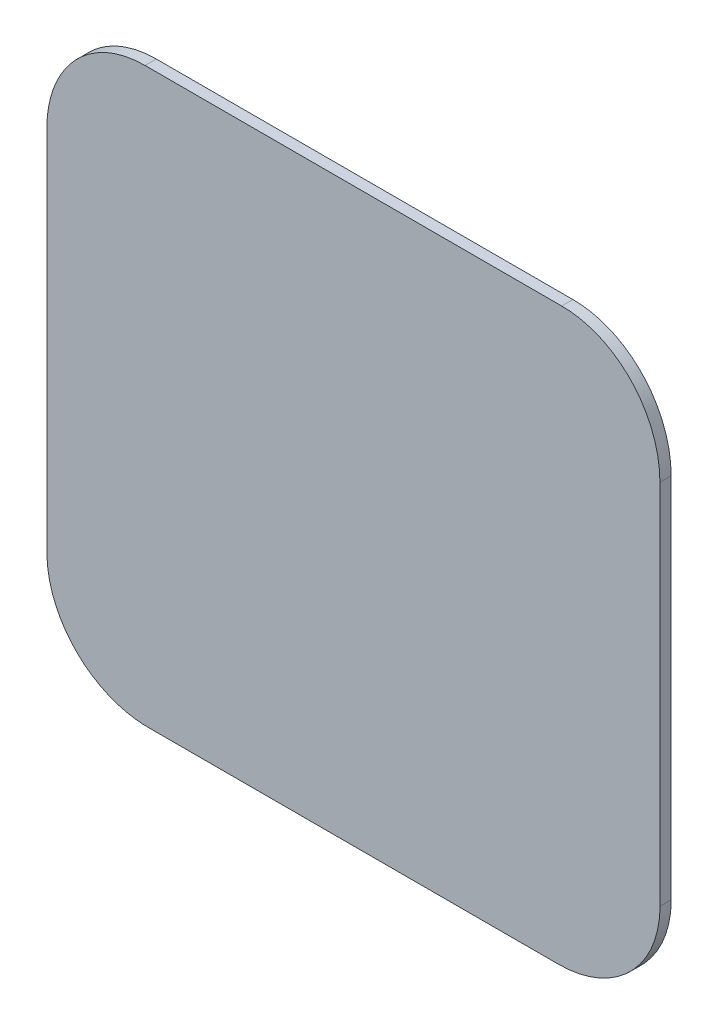
SolidWorks part; units mm, degrees
material "Beech"
ref_plane "Front Plane" through (0, 0, 0) normal (0, 0, 1) x (1, 0, 0)
ref_plane "Top Plane" through (0, 0, 0) normal (0, 1, 0) x (1, 0, 0)
ref_plane "Right Plane" through (0, 0, 0) normal (1, 0, 0) x (0, 0, -1)
sketch "Sketch1" plane through (0, 0, 0) normal (0, 0, 1) x (1, 0, 0)
  line L0 (-105.3184, 124.9067) -> (-105.3184, -72.5)
  line L1 (-105.3184, -72.5) -> (103.4563, -72.5)
  line L2 (103.4563, -72.5) -> (103.4563, 124.9067)
  line L3 (103.4563, 124.9067) -> (-105.3184, 124.9067)
  line L4 (-80, 72.5) -> (-80, -72.5)
  line L5 (-80, -72.5) -> (80, -72.5)
  line L6 (80, -72.5) -> (80, 72.5)
  line L7 (80, 72.5) -> (-80, 72.5)
  line L8 (-80, 72.5) -> (-80, -72.5) construction
  line L9 (-80, -72.5) -> (80, -72.5) construction
  line L10 (80, -72.5) -> (80, 72.5) construction
  point P6 (103.4563, -72.5)
  point P11 (-105.3184, -72.5)
  point P12 (-26.5962, 65.6232)
  point P25 (-25, 60.7089)
  dimension "D1" = 0
extrude "Boss-Extrude1" add sketch "Sketch1" along normal blind 3
sketch3d "3DSketch1"
  line L0 (-81.9859, -42.5, 3) -> (-81.9859, 55.6964, 3)
  line L1 (-81.9859, -42.5, 3) -> (-81.9859, 55.6964, 3)
  line L2 (55.7121, 83.4001, 3) -> (-55.7121, 83.4001, 3)
  line L3 (55.7121, 83.4001, 3) -> (-55.7121, 83.4001, 3)
  line L4 (81.9859, 55.6964, 3) -> (81.9859, -42.5, 3)
  line L5 (81.9859, 55.6964, 3) -> (81.9859, -42.5, 3)
  line L7 (-57.3103, -69.3887, 3) -> (54.8518, -69.5, 2.9231)
  spline S0 degree 3 poles (1820.8216, -546.1374, 3) (335.0368, -201.7655, 3) (-98.3461, -32.8647, 3) (-81.3627, 61.8369, 3) (-81.1687, 62.6966, 3) (-80.8177, 63.9762, 3) (-80.6907, 64.401, 3) (-80.4161, 65.2473, 3) (-80.2683, 65.6692, 3) (-79.4853, 67.7479, 3) (-78.7138, 69.3299, 3) (-77.3377, 71.581, 3) (-76.8423, 72.3109, 3) (-75.7748, 73.7279, 3) (-75.2005, 74.4167, 3) (-73.3997, 76.3696, 3) (-72.0849, 77.5372, 3) (-69.9389, 79.0843, 3) (-69.1937, 79.5661, 3) (-67.6448, 80.4559, 3) (-66.8542, 80.8565, 3) (-64.4352, 81.9294, 3) (-62.7601, 82.474, 3) (-60.5861, 82.9359, 3) (-60.1462, 83.0173, 3) (-59.265, 83.1566, 3) (-58.8233, 83.2146, 3) (40.0623, 93.5712, 3) (189.0947, -468.1443, 3) (411.2832, -1857.0498, 3) knots -6.645974 -6.645974 -6.645974 -6.645974 0.125 0.125 0.1875 0.1875 0.21875 0.21875 0.25 0.25 0.375 0.375 0.4375 0.4375 0.5 0.5 0.625 0.625 0.6875 0.6875 0.75 0.75 0.875 0.875 0.90625 0.90625 0.9375 0.9375 7.886578 7.886578 7.886578 7.886578 only from (-81.9859, 55.6964, 3) to (-55.7121, 83.4001, 3)
  spline S1 degree 3 poles (-81.9859, 55.6964, 3) (-81.9859, 57.4805, 3) (-81.8287, 59.2384, 3) (-81.3627, 61.8369, 3) (-81.1687, 62.6966, 3) (-80.8177, 63.9762, 3) (-80.6907, 64.401, 3) (-80.4161, 65.2473, 3) (-80.2683, 65.6692, 3) (-79.4853, 67.7479, 3) (-78.7138, 69.3299, 3) (-77.3377, 71.581, 3) (-76.8423, 72.3109, 3) (-75.7748, 73.7279, 3) (-75.2005, 74.4167, 3) (-73.3997, 76.3696, 3) (-72.0849, 77.5372, 3) (-69.9389, 79.0843, 3) (-69.1937, 79.5661, 3) (-67.6448, 80.4559, 3) (-66.8542, 80.8565, 3) (-64.4352, 81.9294, 3) (-62.7601, 82.474, 3) (-60.5861, 82.9359, 3) (-60.1462, 83.0173, 3) (-59.265, 83.1566, 3) (-58.8233, 83.2146, 3) (-57.4952, 83.3537, 3) (-56.6057, 83.4001, 3) (-55.7121, 83.4001, 3) knots 0 0 0 0 0.125 0.125 0.1875 0.1875 0.21875 0.21875 0.25 0.25 0.375 0.375 0.4375 0.4375 0.5 0.5 0.625 0.625 0.6875 0.6875 0.75 0.75 0.875 0.875 0.90625 0.90625 0.9375 0.9375 1 1 1 1
  spline S2 degree 3 poles (-528.9221, -1825.3944, 3) (-184.3393, -319.6628, 3) (-24.3861, 100.8215, 3) (61.8362, 82.6719, 3) (62.6902, 82.4455, 3) (63.9595, 82.0364, 3) (64.3815, 81.8881, 3) (65.2121, 81.5713, 3) (65.6217, 81.4027, 3) (67.6418, 80.509, 3) (69.1693, 79.6343, 3) (71.3289, 78.0845, 3) (72.0292, 77.5252, 3) (73.3559, 76.3503, 3) (74.6158, 75.1151, 3) (75.7463, 73.7631, 3) (76.5459, 72.7055, 3) (76.8044, 72.3457, 3) (77.3052, 71.6114, 3) (77.5479, 71.2361, 3) (78.709, 69.3415, 3) (79.4804, 67.7568, 3) (80.415, 65.282, 3) (80.6891, 64.4407, 3) (81.1619, 62.725, 3) (81.3588, 61.8562, 3) (101.0439, -47.6059, 3) (-486.6496, -233.904, 3) (-1829.4053, -516.8289, 3) knots -6.06625 -6.06625 -6.06625 -6.06625 0.125 0.125 0.1875 0.1875 0.21875 0.21875 0.25 0.25 0.375 0.375 0.4375 0.4375 0.5 0.5625 0.5625 0.59375 0.59375 0.625 0.625 0.75 0.75 0.8125 0.8125 0.875 0.875 8.663755 8.663755 8.663755 8.663755 only from (55.7121, 83.4001, 3) to (81.9859, 55.6964, 3)
  spline S3 degree 3 poles (55.7121, 83.4001, 3) (57.4972, 83.4001, 3) (59.2511, 83.2161, 3) (61.8362, 82.6719, 3) (62.6902, 82.4455, 3) (63.9595, 82.0364, 3) (64.3815, 81.8881, 3) (65.2121, 81.5713, 3) (65.6217, 81.4027, 3) (67.6418, 80.509, 3) (69.1693, 79.6343, 3) (71.3289, 78.0845, 3) (72.0292, 77.5252, 3) (73.3559, 76.3503, 3) (74.6158, 75.1151, 3) (75.7463, 73.7631, 3) (76.5459, 72.7055, 3) (76.8044, 72.3457, 3) (77.3052, 71.6114, 3) (77.5479, 71.2361, 3) (78.709, 69.3415, 3) (79.4804, 67.7568, 3) (80.415, 65.282, 3) (80.6891, 64.4407, 3) (81.1619, 62.725, 3) (81.3588, 61.8562, 3) (81.8289, 59.242, 3) (81.9859, 57.4793, 3) (81.9859, 55.6964, 3) knots 0 0 0 0 0.125 0.125 0.1875 0.1875 0.21875 0.21875 0.25 0.25 0.375 0.375 0.4375 0.4375 0.5 0.5625 0.5625 0.59375 0.59375 0.625 0.625 0.75 0.75 0.8125 0.8125 0.875 0.875 1 1 1 1
  spline S4 degree 3 poles (-1829.33, 534.0708, 0.1379) (-272.689, 183.4966, 2.5914) (97.9924, 34.891, 3.1086) (81.2915, -48.6371, 2.9924) (81.0761, -49.494, 2.9912) (80.558, -51.193, 2.9885) (80.2541, -52.037, 2.9871) (79.2303, -54.4912, 2.9827) (78.3951, -56.0428, 2.9796) (77.1621, -57.8776, 2.9754) (76.906, -58.2393, 2.9746) (76.3743, -58.9519, 2.9729) (76.098, -59.3038, 2.9721) (75.2465, -60.3345, 2.9695) (74.6493, -60.9884, 2.9677) (72.7714, -62.8535, 2.9624) (71.4054, -63.9693, 2.9588) (69.5521, -65.2005, 2.9542) (69.1732, -65.439, 2.9532) (68.4083, -65.8945, 2.9514) (68.0217, -66.112, 2.9504) (66.8492, -66.7346, 2.9477) (65.2528, -67.4846, 2.944) (63.591, -68.0769, 2.9404) (62.3198, -68.4612, 2.9377) (61.8919, -68.5793, 2.9368) (61.0277, -68.7951, 2.935) (60.591, -68.8928, 2.9341) (-41.1771, -89.06, 2.7294) (-208.0924, 470.357, 3.0035) (-468.5475, 1856.2863, 3.9593) knots -5.853401 -5.853401 -5.853401 -5.853401 0.125 0.125 0.1875 0.1875 0.25 0.25 0.375 0.375 0.40625 0.40625 0.4375 0.4375 0.5 0.5 0.625 0.625 0.65625 0.65625 0.6875 0.6875 0.75 0.8125 0.8125 0.84375 0.84375 0.875 0.875 8.12185 8.12185 8.12185 8.12185 only from (81.9859, -42.5, 3) to (54.8518, -69.5, 2.9231)
  spline S5 degree 3 poles (81.9859, -42.5, 3) (81.9862, -44.2873, 2.9982) (81.8099, -46.0445, 2.996) (81.2915, -48.6371, 2.9924) (81.0761, -49.494, 2.9912) (80.558, -51.193, 2.9885) (80.2541, -52.037, 2.9871) (79.2303, -54.4912, 2.9827) (78.3951, -56.0428, 2.9796) (77.1621, -57.8776, 2.9754) (76.906, -58.2393, 2.9746) (76.3743, -58.9519, 2.9729) (76.098, -59.3038, 2.9721) (75.2465, -60.3345, 2.9695) (74.6493, -60.9884, 2.9677) (72.7714, -62.8535, 2.9624) (71.4054, -63.9693, 2.9588) (69.5521, -65.2005, 2.9542) (69.1732, -65.439, 2.9532) (68.4083, -65.8945, 2.9514) (68.0217, -66.112, 2.9504) (66.8492, -66.7346, 2.9477) (65.2528, -67.4846, 2.944) (63.591, -68.0769, 2.9404) (62.3198, -68.4612, 2.9377) (61.8919, -68.5793, 2.9368) (61.0277, -68.7951, 2.935) (60.591, -68.8928, 2.9341) (58.4062, -69.3258, 2.9298) (56.6388, -69.4997, 2.9264) (54.8518, -69.5, 2.9231) knots 0 0 0 0 0.125 0.125 0.1875 0.1875 0.25 0.25 0.375 0.375 0.40625 0.40625 0.4375 0.4375 0.5 0.5 0.625 0.625 0.65625 0.65625 0.6875 0.6875 0.75 0.8125 0.8125 0.84375 0.84375 0.875 0.875 1 1 1 1
  spline S6 degree 3 poles (1829.2313, 534.3813, 3) (272.6605, 183.5658, 3) (-98.0057, 34.895, 3) (-81.2905, -48.6379, 3) (-81.0749, -49.4949, 3) (-80.5565, -51.1941, 3) (-80.2523, -52.0382, 3) (-79.228, -54.4927, 3) (-78.3924, -56.0444, 3) (-77.159, -57.8793, 3) (-76.9028, -58.2409, 3) (-76.3709, -58.9536, 3) (-76.0945, -59.3055, 3) (-75.2428, -60.3362, 3) (-74.6453, -60.9901, 3) (-72.7668, -62.8553, 3) (-71.4005, -63.9709, 3) (-69.5467, -65.2021, 3) (-69.1677, -65.4405, 3) (-68.4027, -65.896, 3) (-68.0159, -66.1135, 3) (-66.8432, -66.736, 3) (-65.2464, -67.4858, 3) (-63.5842, -68.078, 3) (-62.3128, -68.4622, 3) (-61.8848, -68.5802, 3) (-61.0204, -68.7959, 3) (-60.5836, -68.8936, 3) (41.1964, -89.047, 3) (208.0355, 470.4038, 3) (468.2869, 1856.3789, 3) knots -5.853011 -5.853011 -5.853011 -5.853011 0.125 0.125 0.1875 0.1875 0.25 0.25 0.375 0.375 0.40625 0.40625 0.4375 0.4375 0.5 0.5 0.625 0.625 0.65625 0.65625 0.6875 0.6875 0.75 0.8125 0.8125 0.84375 0.84375 0.875 0.875 8.121359 8.121359 8.121359 8.121359 only from (-81.9859, -42.5, 3) to (-54.8435, -69.5, 3)
  spline S7 degree 3 poles (-81.9859, -42.5, 3) (-81.9859, -44.2876, 3) (-81.8093, -46.045, 3) (-81.2905, -48.6379, 3) (-81.0749, -49.4949, 3) (-80.5565, -51.1941, 3) (-80.2523, -52.0382, 3) (-79.228, -54.4927, 3) (-78.3924, -56.0444, 3) (-77.159, -57.8793, 3) (-76.9028, -58.2409, 3) (-76.3709, -58.9536, 3) (-76.0945, -59.3055, 3) (-75.2428, -60.3362, 3) (-74.6453, -60.9901, 3) (-72.7668, -62.8553, 3) (-71.4005, -63.9709, 3) (-69.5467, -65.2021, 3) (-69.1677, -65.4405, 3) (-68.4027, -65.896, 3) (-68.0159, -66.1135, 3) (-66.8432, -66.736, 3) (-65.2464, -67.4858, 3) (-63.5842, -68.078, 3) (-62.3128, -68.4622, 3) (-61.8848, -68.5802, 3) (-61.0204, -68.7959, 3) (-60.5836, -68.8936, 3) (-59.2068, -69.1662, 3) (-58.2613, -69.3025, 3) (-57.3103, -69.3887, 3) knots 0 0 0 0 0.125 0.125 0.1875 0.1875 0.25 0.25 0.375 0.375 0.40625 0.40625 0.4375 0.4375 0.5 0.5 0.625 0.625 0.65625 0.65625 0.6875 0.6875 0.75 0.8125 0.8125 0.84375 0.84375 0.875 0.875 0.942199 0.942199 0.942199 0.942199
sketch "Sketch3" plane through (0, 0, 3) normal (0, 0, 1) x (1, 0, 0)
  line L0 (-81.9859, -42.5) -> (-81.9859, 55.6964) construction
  line L1 (81.9859, 55.6964) -> (81.9859, -42.5) construction
  line L2 (55.7121, 83.4001) -> (-55.7121, 83.4001) construction
  line L3 (-81.9859, -42.5) -> (-81.9859, 55.6964)
  line L4 (81.9859, 55.6964) -> (81.9859, -42.5)
  line L5 (55.7121, 83.4001) -> (-55.7121, 83.4001)
  line L6 (-54.8435, -69.5) -> (54.8518, -69.5)
  spline S0 degree 3 poles (-1829.33, 534.0708) (-272.689, 183.4966) (97.9924, 34.891) (81.2915, -48.6371) (81.0761, -49.494) (80.558, -51.193) (80.2541, -52.037) (79.2303, -54.4912) (78.3951, -56.0428) (77.1621, -57.8776) (76.906, -58.2393) (76.3743, -58.9519) (76.098, -59.3038) (75.2465, -60.3345) (74.6493, -60.9884) (72.7714, -62.8535) (71.4054, -63.9693) (69.5521, -65.2005) (69.1732, -65.439) (68.4083, -65.8945) (68.0217, -66.112) (66.8492, -66.7346) (65.2528, -67.4846) (63.591, -68.0769) (62.3198, -68.4612) (61.8919, -68.5793) (61.0277, -68.7951) (60.591, -68.8928) (-41.1771, -89.06) (-208.0924, 470.357) (-468.5475, 1856.2863) knots -5.853401 -5.853401 -5.853401 -5.853401 0.125 0.125 0.1875 0.1875 0.25 0.25 0.375 0.375 0.40625 0.40625 0.4375 0.4375 0.5 0.5 0.625 0.625 0.65625 0.65625 0.6875 0.6875 0.75 0.8125 0.8125 0.84375 0.84375 0.875 0.875 8.12185 8.12185 8.12185 8.12185 only from (81.9859, -42.5) to (54.8518, -69.5) construction
  spline S1 degree 3 poles (1829.2532, 534.3863) (272.664, 183.5672) (-98.0057, 34.8954) (-81.2905, -48.6379) (-81.0749, -49.4949) (-80.5565, -51.1941) (-80.2523, -52.0382) (-79.228, -54.4927) (-78.3924, -56.0444) (-77.159, -57.8793) (-76.9028, -58.2409) (-76.3709, -58.9536) (-76.0945, -59.3055) (-75.2428, -60.3362) (-74.6453, -60.9901) (-72.7668, -62.8553) (-71.4005, -63.9709) (-69.5467, -65.2021) (-69.1677, -65.4405) (-68.4027, -65.896) (-68.0159, -66.1135) (-66.8432, -66.736) (-65.2464, -67.4858) (-63.5842, -68.078) (-62.3128, -68.4622) (-61.8848, -68.5802) (-61.0204, -68.7959) (-60.5836, -68.8936) (41.1795, -89.0437) (207.9797, 470.2167) (468.1563, 1855.6835) knots -5.853039 -5.853039 -5.853039 -5.853039 0.125 0.125 0.1875 0.1875 0.25 0.25 0.375 0.375 0.40625 0.40625 0.4375 0.4375 0.5 0.5 0.625 0.625 0.65625 0.65625 0.6875 0.6875 0.75 0.8125 0.8125 0.84375 0.84375 0.875 0.875 8.120147 8.120147 8.120147 8.120147 only from (-81.9859, -42.5) to (-57.3103, -69.3887) construction
  spline S2 degree 3 poles (-528.9221, -1825.3944) (-184.3393, -319.6628) (-24.3861, 100.8215) (61.8362, 82.6719) (62.6902, 82.4455) (63.9595, 82.0364) (64.3815, 81.8881) (65.2121, 81.5713) (65.6217, 81.4027) (67.6418, 80.509) (69.1693, 79.6343) (71.3289, 78.0845) (72.0292, 77.5252) (73.3559, 76.3503) (74.6158, 75.1151) (75.7463, 73.7631) (76.5459, 72.7055) (76.8044, 72.3457) (77.3052, 71.6114) (77.5479, 71.2361) (78.709, 69.3415) (79.4804, 67.7568) (80.415, 65.282) (80.6891, 64.4407) (81.1619, 62.725) (81.3588, 61.8562) (101.0439, -47.6059) (-486.6496, -233.904) (-1829.4053, -516.8289) knots -6.06625 -6.06625 -6.06625 -6.06625 0.125 0.125 0.1875 0.1875 0.21875 0.21875 0.25 0.25 0.375 0.375 0.4375 0.4375 0.5 0.5625 0.5625 0.59375 0.59375 0.625 0.625 0.75 0.75 0.8125 0.8125 0.875 0.875 8.663755 8.663755 8.663755 8.663755 only from (55.7121, 83.4001) to (81.9859, 55.6964) construction
  spline S3 degree 3 poles (1820.8216, -546.1374) (335.0368, -201.7655) (-98.3461, -32.8647) (-81.3627, 61.8369) (-81.1687, 62.6966) (-80.8177, 63.9762) (-80.6907, 64.401) (-80.4161, 65.2473) (-80.2683, 65.6692) (-79.4853, 67.7479) (-78.7138, 69.3299) (-77.3377, 71.581) (-76.8423, 72.3109) (-75.7748, 73.7279) (-75.2005, 74.4167) (-73.3997, 76.3696) (-72.0849, 77.5372) (-69.9389, 79.0843) (-69.1937, 79.5661) (-67.6448, 80.4559) (-66.8542, 80.8565) (-64.4352, 81.9294) (-62.7601, 82.474) (-60.5861, 82.9359) (-60.1462, 83.0173) (-59.265, 83.1566) (-58.8233, 83.2146) (40.0623, 93.5712) (189.0947, -468.1443) (411.2832, -1857.0498) knots -6.645974 -6.645974 -6.645974 -6.645974 0.125 0.125 0.1875 0.1875 0.21875 0.21875 0.25 0.25 0.375 0.375 0.4375 0.4375 0.5 0.5 0.625 0.625 0.6875 0.6875 0.75 0.75 0.875 0.875 0.90625 0.90625 0.9375 0.9375 7.886578 7.886578 7.886578 7.886578 only from (-81.9859, 55.6964) to (-55.7121, 83.4001) construction
  spline S4 degree 3 poles (81.9859, -42.5) (81.9862, -44.2873) (81.8099, -46.0445) (81.2915, -48.6371) (81.0761, -49.494) (80.558, -51.193) (80.2541, -52.037) (79.2303, -54.4912) (78.3951, -56.0428) (77.1621, -57.8776) (76.906, -58.2393) (76.3743, -58.9519) (76.098, -59.3038) (75.2465, -60.3345) (74.6493, -60.9884) (72.7714, -62.8535) (71.4054, -63.9693) (69.5521, -65.2005) (69.1732, -65.439) (68.4083, -65.8945) (68.0217, -66.112) (66.8492, -66.7346) (65.2528, -67.4846) (63.591, -68.0769) (62.3198, -68.4612) (61.8919, -68.5793) (61.0277, -68.7951) (60.591, -68.8928) (58.4062, -69.3258) (56.6388, -69.4997) (54.8518, -69.5) knots 0 0 0 0 0.125 0.125 0.1875 0.1875 0.25 0.25 0.375 0.375 0.40625 0.40625 0.4375 0.4375 0.5 0.5 0.625 0.625 0.65625 0.65625 0.6875 0.6875 0.75 0.8125 0.8125 0.84375 0.84375 0.875 0.875 1 1 1 1
  spline S5 degree 3 poles (-81.9859, -42.5) (-81.9859, -44.2876) (-81.8093, -46.045) (-81.2905, -48.6379) (-81.0749, -49.4949) (-80.5565, -51.1941) (-80.2523, -52.0382) (-79.228, -54.4927) (-78.3924, -56.0444) (-77.159, -57.8793) (-76.9028, -58.2409) (-76.3709, -58.9536) (-76.0945, -59.3055) (-75.2428, -60.3362) (-74.6453, -60.9901) (-72.7668, -62.8553) (-71.4005, -63.9709) (-69.5467, -65.2021) (-69.1677, -65.4405) (-68.4027, -65.896) (-68.0159, -66.1135) (-66.8432, -66.736) (-65.2464, -67.4858) (-63.5842, -68.078) (-62.3128, -68.4622) (-61.8848, -68.5802) (-61.0204, -68.7959) (-60.5836, -68.8936) (-58.3984, -69.3263) (-56.6307, -69.5) (-54.8435, -69.5) knots 0 0 0 0 0.125 0.125 0.1875 0.1875 0.25 0.25 0.375 0.375 0.40625 0.40625 0.4375 0.4375 0.5 0.5 0.625 0.625 0.65625 0.65625 0.6875 0.6875 0.75 0.8125 0.8125 0.84375 0.84375 0.875 0.875 1 1 1 1
  spline S6 degree 3 poles (55.7121, 83.4001) (57.4972, 83.4001) (59.2511, 83.2161) (61.8362, 82.6719) (62.6902, 82.4455) (63.9595, 82.0364) (64.3815, 81.8881) (65.2121, 81.5713) (65.6217, 81.4027) (67.6418, 80.509) (69.1693, 79.6343) (71.3289, 78.0845) (72.0292, 77.5252) (73.3559, 76.3503) (74.6158, 75.1151) (75.7463, 73.7631) (76.5459, 72.7055) (76.8044, 72.3457) (77.3052, 71.6114) (77.5479, 71.2361) (78.709, 69.3415) (79.4804, 67.7568) (80.415, 65.282) (80.6891, 64.4407) (81.1619, 62.725) (81.3588, 61.8562) (81.8289, 59.242) (81.9859, 57.4793) (81.9859, 55.6964) knots 0 0 0 0 0.125 0.125 0.1875 0.1875 0.21875 0.21875 0.25 0.25 0.375 0.375 0.4375 0.4375 0.5 0.5625 0.5625 0.59375 0.59375 0.625 0.625 0.75 0.75 0.8125 0.8125 0.875 0.875 1 1 1 1
  spline S7 degree 3 poles (-81.9859, 55.6964) (-81.9859, 57.4805) (-81.8287, 59.2384) (-81.3627, 61.8369) (-81.1687, 62.6966) (-80.8177, 63.9762) (-80.6907, 64.401) (-80.4161, 65.2473) (-80.2683, 65.6692) (-79.4853, 67.7479) (-78.7138, 69.3299) (-77.3377, 71.581) (-76.8423, 72.3109) (-75.7748, 73.7279) (-75.2005, 74.4167) (-73.3997, 76.3696) (-72.0849, 77.5372) (-69.9389, 79.0843) (-69.1937, 79.5661) (-67.6448, 80.4559) (-66.8542, 80.8565) (-64.4352, 81.9294) (-62.7601, 82.474) (-60.5861, 82.9359) (-60.1462, 83.0173) (-59.265, 83.1566) (-58.8233, 83.2146) (-57.4952, 83.3537) (-56.6057, 83.4001) (-55.7121, 83.4001) knots 0 0 0 0 0.125 0.125 0.1875 0.1875 0.21875 0.21875 0.25 0.25 0.375 0.375 0.4375 0.4375 0.5 0.5 0.625 0.625 0.6875 0.6875 0.75 0.75 0.875 0.875 0.90625 0.90625 0.9375 0.9375 1 1 1 1
  point P4 (-55.7121, -69.5)
extrude "Cut-Extrude1" cut sketch "Sketch3" against normal through all both and the other way through all flip side to cut
